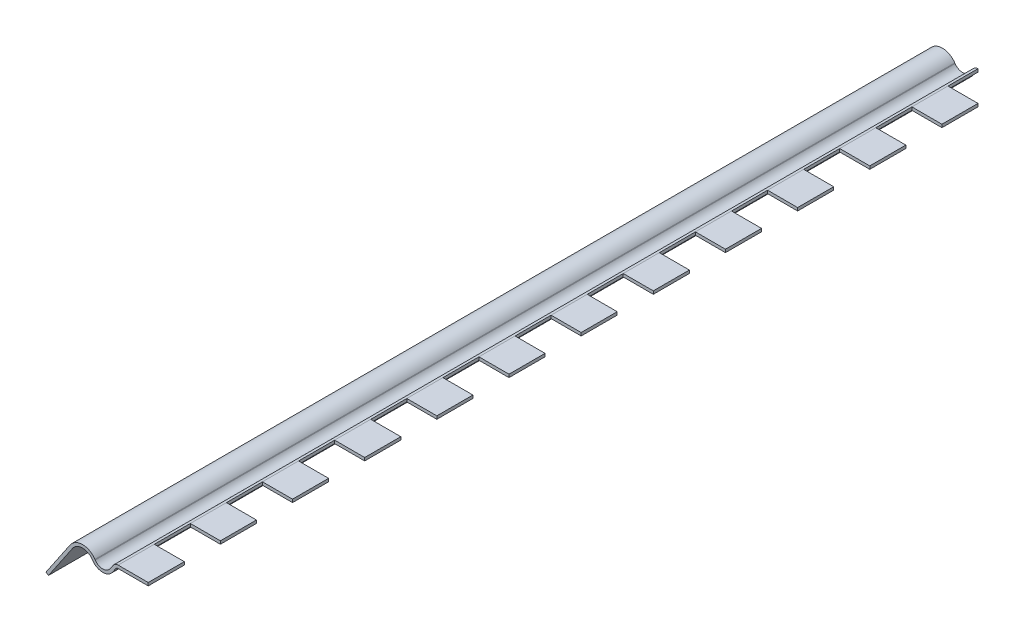
SolidWorks part; units mm, degrees
ref_plane "Front Plane" through (0, 0, 0) normal (0, 0, 1) x (1, 0, 0)
ref_plane "Top Plane" through (0, 0, 0) normal (0, 1, 0) x (1, 0, 0)
ref_plane "Right Plane" through (0, 0, 0) normal (1, 0, 0) x (0, 0, -1)
sketch "Sketch1" plane through (0, 0, 0) normal (0, 0, 1) x (1, 0, 0)
  line L0 (0, 0) -> (-5, 0)
  line L1 (-5.8275, -0.4386) -> (-6.3241, -1.1705)
  line L2 (-8.8067, -1.1705) -> (-8.857, -1.0964)
  line L3 (-12.9945, -1.0964) -> (-17, -7)
  line L4 (-5.53, 0) -> (-10.9257, 0) construction
  line L5 (0, -0.5) -> (-5, -0.5)
  line L6 (-5.4138, -0.7193) -> (-5.9104, -1.4512)
  line L7 (-9.2204, -1.4512) -> (-9.2707, -1.3771)
  line L8 (-12.5808, -1.3771) -> (-16.5862, -7.2807)
  line L9 (-17, -7) -> (-16.5862, -7.2807)
  line L10 (0, 0) -> (0, -0.5)
  arc A0 (-8.8067, -1.1705) -> (-6.3241, -1.1705) centre (-7.5654, -0.3283) ccw
  arc A1 (-8.857, -1.0964) -> (-12.9945, -1.0964) centre (-10.9257, -2.5) ccw
  arc A2 (-5.8275, -0.4386) -> (-5, 0) centre (-5, -1) cw
  arc A3 (-5.4138, -0.7193) -> (-5, -0.5) centre (-5, -1) cw
  arc A4 (-9.2204, -1.4512) -> (-5.9104, -1.4512) centre (-7.5654, -0.3283) ccw
  arc A5 (-9.2707, -1.3771) -> (-12.5808, -1.3771) centre (-10.9257, -2.5) ccw
  point P9 (-7.5654, -3)
  point P12 (-10.9257, 1.9528)
  dimension "D4" = 1.5
  dimension "D5" = 2.5
  dimension "D6" = 1
  dimension "D1" = 3
  dimension "D2" = 7
  dimension "D3" = 5
  dimension "D7" = 17
  dimension "D8" = 0.5
extrude "Boss-Extrude1" add sketch "Sketch1" along normal mid plane 143 contours A5 L8 L9 L3 A1 L2 A0 L1 A2 L0 L10 L5 A3 L6 A4 L7
sketch "Sketch3" plane through (0, 0, 0) normal (0, 1, 0) x (1, 0, 0)
  line L0 (0, -65.5) -> (-5, -65.5)
  line L1 (0, -71.5) -> (0, 71.5) construction
  line L2 (-5, -71.5) -> (-5, 71.5) construction
  line L3 (-5, -65.5) -> (-5, -59.5)
  line L4 (-5, -59.5) -> (0, -59.5)
  line L5 (0, -59.5) -> (0, -65.5)
  dimension "D1" = 6
  dimension "D2" = 6
extrude "Cut-Extrude1" cut sketch "Sketch3" against normal through all
pattern_linear "LPattern1" count 12 spacing 12 along (0, 0, -1) of "Cut-Extrude1"
